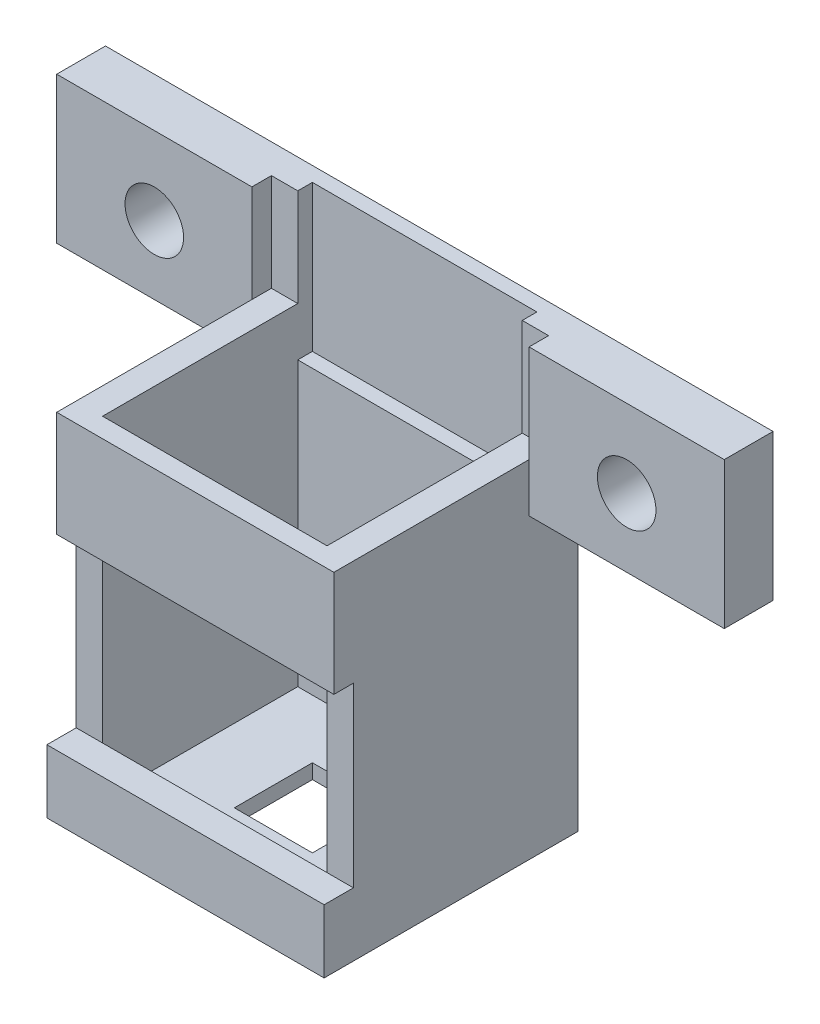
SolidWorks part; units mm, degrees
ref_plane "Front Plane" through (0, 0, 0) normal (0, 0, 1) x (1, 0, 0)
ref_plane "Top Plane" through (0, 0, 0) normal (0, 1, 0) x (1, 0, 0)
ref_plane "Right Plane" through (0, 0, 0) normal (1, 0, 0) x (0, 0, -1)
sketch "Sketch1" plane through (0, 0, 0) normal (0, 1, 0) x (1, 0, 0)
  line L1 (0, 0) -> (23, 0)
  line L2 (0, 0) -> (0, 20)
  line L3 (0, 20) -> (23, 20)
  line L4 (23, 0) -> (23, 20)
  dimension "D1" = 20
  dimension "D2" = 23
extrude "Boss-Extrude1" add sketch "Sketch1" along normal blind 3
sketch "Sketch2" plane through (0, 0, 0) normal (-1, 0, 0) x (0, 0, 1)
  line L1 (0, 0) -> (-20, 0)
  line L2 (0, 0) -> (0, 37)
  line L3 (0, 37) -> (-20, 37)
  line L4 (-20, 0) -> (-20, 37)
  dimension "D1" = 37
extrude "Boss-Extrude2" add sketch "Sketch2" along normal blind 2.7
sketch "Sketch3" plane through (23, 0, 0) normal (1, 0, 0) x (0, 0, -1)
  line L1 (0, 0) -> (20, 0)
  line L2 (0, 0) -> (0, 37)
  line L3 (0, 37) -> (20, 37)
  line L4 (20, 0) -> (20, 37)
extrude "Boss-Extrude3" add sketch "Sketch3" along normal blind 2.7
sketch "Sketch4" plane through (0, 0, 0) normal (0, 0, 1) x (1, 0, 0)
  line L0 (25.7, 37) -> (25.7, 0) construction
  line L1 (-2.7, 0) -> (25.7, 0)
  line L2 (-2.7, 0) -> (-2.7, 8)
  line L3 (-2.7, 8) -> (25.7, 8)
  line L4 (25.7, 0) -> (25.7, 8)
  dimension "D1" = 8
extrude "Boss-Extrude4" add sketch "Sketch4" along normal blind 3
sketch "Sketch5" plane through (0, 0, -20) normal (0, 0, -1) x (-1, 0, 0)
  line L1 (-25.7, 47) -> (2.7, 47)
  line L2 (-25.7, 47) -> (-25.7, 0)
  line L3 (-25.7, 0) -> (2.7, 0)
  line L4 (2.7, 47) -> (2.7, 0)
  dimension "D1" = 47
extrude "Boss-Extrude5" add sketch "Sketch5" along normal blind 3
sketch "Sketch6" plane through (25.7, 0, 0) normal (1, 0, 0) x (0, 0, -1)
  line L1 (23, 47) -> (18, 47)
  line L2 (23, 47) -> (23, 32)
  line L3 (23, 32) -> (18, 32)
  line L4 (18, 47) -> (18, 32)
  dimension "D1" = 5
  dimension "D2" = 15
extrude "Boss-Extrude6" add sketch "Sketch6" along normal blind 20
sketch "Sketch7" plane through (-2.7, 0, 0) normal (-1, 0, 0) x (0, 0, 1)
  line L1 (-23, 47) -> (-18, 47)
  line L2 (-23, 47) -> (-23, 32)
  line L3 (-23, 32) -> (-18, 32)
  line L4 (-18, 47) -> (-18, 32)
  dimension "D1" = 5
  dimension "D2" = 15
extrude "Boss-Extrude7" add sketch "Sketch7" along normal blind 20
sketch "Sketch8" plane through (0, 3, 0) normal (0, 1, 0) x (1, 0, 0)
  line L0 (23, 20) -> (0, 20) construction
  line L1 (7.5, 6) -> (15.5, 6)
  line L2 (7.5, 6) -> (7.5, 14)
  line L3 (7.5, 14) -> (15.5, 14)
  line L4 (15.5, 6) -> (15.5, 14)
  line L5 (0, 20) -> (0, 0) construction
  point P4 (11.5, 14)
  point P7 (11.5, 20)
  point P8 (7.5, 10)
  point P11 (0, 10)
  dimension "D1" = 0
  dimension "D2" = 0
  dimension "D3" = 8
  dimension "D4" = 8
extrude "Cut-Extrude1" cut sketch "Sketch8" against normal blind 15
sketch "Sketch9" plane through (0, 0, -18) normal (0, 0, 1) x (1, 0, 0)
  line L0 (25.7, 47) -> (25.7, 37) construction
  line L1 (-2.7, 37) -> (-2.7, 47) construction
  line L2 (-22.7, 32) -> (-2.7, 32) construction
  line L3 (45.7, 32) -> (25.7, 32) construction
  circle A0 centre (-12.7, 39) radius 3
  circle A1 centre (35.7, 39) radius 3
  dimension "D1" = 6
  dimension "D4" = 7
  dimension "D5" = 7
  dimension "D6" = 6
  dimension "D2" = 10
  dimension "D3" = 10
extrude "Cut-Extrude2" cut sketch "Sketch9" against normal blind 15
sketch "Sketch10" plane through (0, 0, 0) normal (0, -1, 0) x (1, 0, 0)
  line L1 (-2.7, 3) -> (25.75, 3)
  line L2 (-2.7, 3) -> (-2.7, -23)
  line L3 (-2.7, -23) -> (25.75, -23)
  line L4 (25.75, 3) -> (25.75, -23)
extrude "Cut-Extrude3" cut sketch "Sketch10" against normal blind 1.5
sketch "Sketch12" plane through (0, 47, 0) normal (0, 1, 0) x (1, 0, 0)
  line L1 (0, 20) -> (23, 20)
  line L2 (0, 20) -> (0, 21.5)
  line L3 (0, 21.5) -> (23, 21.5)
  line L4 (23, 20) -> (23, 21.5)
  dimension "D1" = 1.5
extrude "Cut-Extrude4" cut sketch "Sketch12" against normal blind 15
sketch "Sketch13" plane through (0, 0, 0) normal (0, 0, 1) x (1, 0, 0)
  line L0 (-2.7, 8) -> (-2.7, 37) construction
  line L1 (25.7, 37) -> (-2.7, 37)
  line L2 (25.7, 37) -> (25.7, 26.1637)
  line L3 (25.7, 26.1637) -> (-2.7, 26.1637)
  line L4 (-2.7, 37) -> (-2.7, 26.1637)
extrude "Boss-Extrude8" add sketch "Sketch13" along normal blind 2
